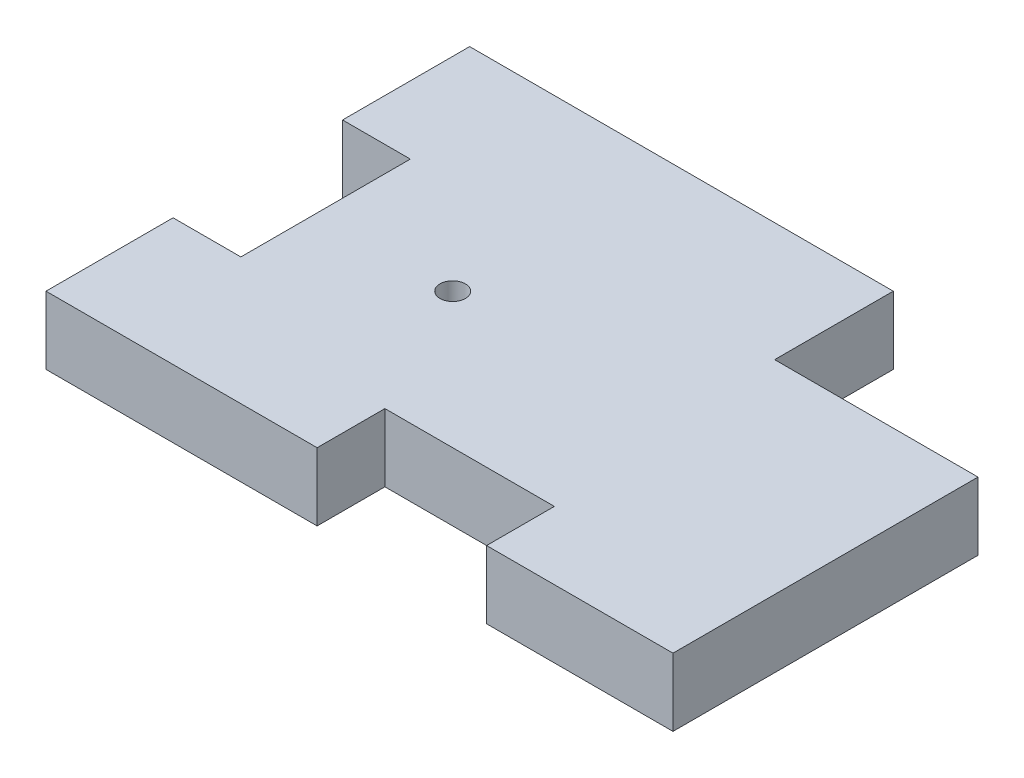
SolidWorks part; units mm, degrees
material "Maple"
ref_plane "Front Plane" through (0, 0, 0) normal (0, 0, 1) x (1, 0, 0)
ref_plane "Top Plane" through (0, 0, 0) normal (0, 1, 0) x (1, 0, 0)
ref_plane "Right Plane" through (0, 0, 0) normal (1, 0, 0) x (0, 0, -1)
sketch "Sketch1" plane through (0, 0, 0) normal (0, 1, 0) x (1, 0, 0)
  line L1 (0, 0) -> (37, 0)
  line L2 (0, 0) -> (0, -25)
  line L3 (0, -25) -> (37, -25)
  line L4 (37, 0) -> (37, -25)
  dimension "D1" = 37
  dimension "D2" = 25
extrude "Boss-Extrude1" add sketch "Sketch1" along normal blind 4
sketch "Sketch2" plane through (0, 4, 0) normal (0, 1, 0) x (1, 0, 0)
  line L0 (37, 0) -> (0, 0) construction
  line L1 (37, 0) -> (25, 0)
  line L2 (37, 0) -> (37, -7)
  line L3 (37, -7) -> (25, -7)
  line L4 (25, 0) -> (25, -7)
  line L5 (37, -25) -> (37, 0) construction
  dimension "D1" = 7
  dimension "D2" = 12
extrude "Cut-Extrude1" cut sketch "Sketch2" against normal through all
sketch "Sketch3" plane through (0, 0, 0) normal (0, -1, 0) x (1, 0, 0)
  line L0 (0, 0) -> (0, 25) construction
  line L1 (4, 7.5) -> (0, 7.5)
  line L2 (4, 7.5) -> (4, 17.5)
  line L3 (4, 17.5) -> (0, 17.5)
  line L4 (0, 7.5) -> (0, 17.5)
extrude "Cut-Extrude2" cut sketch "Sketch3" against normal through all
sketch "Sketch4" plane through (0, 0, 0) normal (0, -1, 0) x (-1, 0, 0)
  line L0 (0, -25) -> (-37, -25) construction
  line L1 (-16, -21) -> (-26, -21)
  line L2 (-16, -21) -> (-16, -25)
  line L3 (-16, -25) -> (-26, -25)
  line L4 (-26, -21) -> (-26, -25)
extrude "Cut-Extrude3" cut sketch "Sketch4" against normal through all
sketch "Sketch5" plane through (0, 4, 0) normal (0, 1, 0) x (1, 0, 0)
  circle A0 centre (12, -13) radius 0.75
  dimension "D1" = 1.5
extrude "Cut-Extrude4" cut sketch "Sketch5" against normal through all
